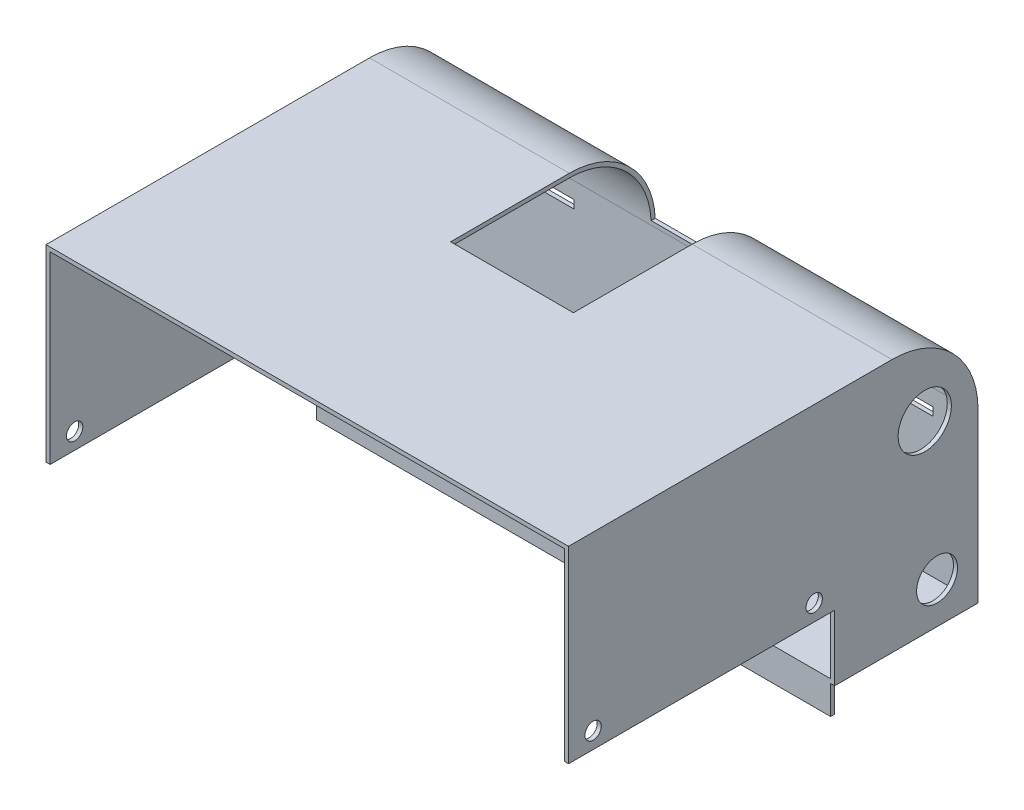
SolidWorks part; units mm, degrees
ref_plane "前视基准面" through (0, 0, 0) normal (0, 0, 1) x (1, 0, 0)
ref_plane "上视基准面" through (0, 0, 0) normal (0, 1, 0) x (1, 0, 0)
ref_plane "右视基准面" through (0, 0, 0) normal (1, 0, 0) x (0, 0, -1)
sketch "草图1" plane through (0, 0, 0) normal (1, 0, 0) x (0, 0, -1)
  line L0 (0, 0) -> (0, 41)
  line L1 (-21, 62) -> (-100, 62)
  line L2 (-100, 62) -> (-100, 61)
  line L6 (0, 0) -> (-34, 0)
  line L7 (-35, -7) -> (-35, 1)
  line L8 (-35, 1) -> (-1, 1)
  line L9 (-1, 1) -> (-1, 41)
  line L10 (-21, 61) -> (-100, 61)
  line L11 (-34, 0) -> (-34, -7)
  line L12 (-34, -7) -> (-35, -7)
  arc A0 (-1, 41) -> (-21, 61) centre (-21, 41) ccw
  arc A1 (0, 41) -> (-21, 62) centre (-21, 41) ccw
  point P15 (0, 62)
  dimension "D7" = 20
  dimension "D8" = 21
  dimension "D1" = 1
  dimension "D2" = 34
  dimension "D3" = 1
  dimension "D4" = 60
  dimension "D5" = 100
  dimension "D6" = 1
  dimension "D9" = 8
  dimension "D10" = 1
extrude "凸台-拉伸1" add sketch "草图1" along normal blind 125.6
sketch "草图2" plane through (0, 0, 0) normal (-1, 0, 0) x (0, 0, 1)
  line L1 (0, 0) -> (0, 41) construction
  line L2 (21, 62) -> (100, 62) construction
  line L3 (35, 0) -> (0, 0)
  line L4 (0, 0) -> (0, 41)
  line L5 (21, 62) -> (100, 62)
  line L6 (100, 62) -> (100, 16)
  line L7 (100, 16) -> (35, 16)
  line L8 (35, 16) -> (35, 0)
  line L9 (35, 1) -> (35, -7) construction
  line L10 (34, 0) -> (0, 0) construction
  line L11 (40, 20) -> (94, 20) construction
  arc A0 (21, 62) -> (0, 41) centre (21, 41) ccw construction
  arc A1 (21, 62) -> (0, 41) centre (21, 41) ccw
  circle A2 centre (94, 20) radius 2
  circle A3 centre (40, 20) radius 2
  dimension "D2" = 4
  dimension "D3" = 4
  dimension "D4" = 54
  dimension "D6" = 20
  dimension "D1" = 16
  dimension "D5" = 5
extrude "凸台-拉伸2" add sketch "草图2" along normal blind 1
sketch "草图3" plane through (125.6, 0, 0) normal (1, 0, 0) x (0, 0, -1)
  line L0 (-35, 16) -> (-100, 16) construction
  line L1 (-35, 0) -> (-35, 16) construction
  line L2 (0, 0) -> (-35, 0) construction
  line L3 (0, 41) -> (0, 0) construction
  line L4 (-100, 62) -> (-21, 62) construction
  line L5 (-100, 16) -> (-100, 62) construction
  line L6 (-35, 16) -> (-100, 16)
  line L7 (-35, 0) -> (-35, 16)
  line L8 (0, 0) -> (-35, 0)
  line L9 (0, 41) -> (0, 0)
  line L10 (-100, 62) -> (-21, 62)
  line L11 (-100, 16) -> (-100, 62)
  circle A0 centre (-94, 20) radius 2 construction
  circle A1 centre (-40, 20) radius 2 construction
  arc A2 (0, 41) -> (-21, 62) centre (-21, 41) ccw construction
  circle A3 centre (-94, 20) radius 2
  circle A4 centre (-40, 20) radius 2
  arc A5 (0, 41) -> (-21, 62) centre (-21, 41) ccw
  circle A6 centre (-13, 45) radius 6.5
  circle A7 centre (-10, 10) radius 5
  dimension "D1" = 13
  dimension "D2" = 10
  dimension "D3" = 13
  dimension "D4" = 45
  dimension "D5" = 10
  dimension "D6" = 10
extrude "凸台-拉伸3" add sketch "草图3" along normal blind 1
sketch "草图4" plane through (0, 62, 0) normal (0, 1, 0) x (1, 0, 0)
  line L0 (62.8, -100) -> (62.8, 31.7599) construction
  line L1 (126.6, -100) -> (-1, -100) construction
  line L2 (47.8, -50) -> (77.8, -50)
  line L3 (77.8, -50) -> (77.8, 0)
  line L4 (77.8, 0) -> (47.8, 0)
  line L5 (47.8, -50) -> (47.8, 0)
  line L6 (126.6, 0) -> (-1, 0) construction
  point P8 (62.8, 0)
  dimension "D1" = 30
  dimension "D2" = 50
extrude "切除-拉伸1" cut sketch "草图4" against normal blind 20
sketch "草图5" plane through (0, 0, 0) normal (0, 0, -1) x (-1, 0, 0)
  line L0 (-62.8, 0) -> (-62.8, 69.7654) construction
  line L1 (-116.6, 37) -> (-96.6, 37)
  line L2 (-116.6, 37) -> (-116.6, 35)
  line L3 (-116.6, 35) -> (-96.6, 35)
  line L4 (-96.6, 37) -> (-96.6, 35)
  line L5 (-126.6, 0) -> (1, 0) construction
  line L6 (-29, 37) -> (-29, 35)
  line L7 (-9, 35) -> (-29, 35)
  line L8 (-9, 37) -> (-9, 35)
  line L9 (-9, 37) -> (-29, 37)
  line L10 (-126.6, 0) -> (-126.6, 41) construction
  line L11 (-126.6, 41) -> (1, 41) construction
  dimension "D1" = 2
  dimension "D2" = 20
  dimension "D3" = 10
  dimension "D4" = 4
extrude "切除-拉伸2" cut sketch "草图5" against normal up to next
sketch "草图6" plane through (126.6, 0, 0) normal (1, 0, 0) x (0, 0, -1)
  line L0 (-10, 16) -> (0, 16)
  line L1 (0, 0) -> (0, 41) construction
  line L2 (0, 16) -> (0, 4)
  line L3 (0, 4) -> (-10, 4)
  line L4 (-11.5529, 15.7956) -> (-11.1647, 14.3467)
  line L5 (-11.1647, 5.6533) -> (-11.5529, 4.2044)
  line L6 (-10, 10) -> (-10, 22.6843) construction
  line L7 (-11.1647, 5.6533) -> (-10, 10) construction
  line L8 (-10, 10) -> (-11.1647, 14.3467) construction
  arc A0 (-11.1647, 5.6533) -> (-11.1647, 14.3467) centre (-10, 10) ccw
  arc A1 (-10, 16) -> (-11.5529, 15.7956) centre (-10, 10) ccw
  arc A2 (-11.5529, 4.2044) -> (-10, 4) centre (-10, 10) ccw
  dimension "D1" = 9
  dimension "D2" = 12
  dimension "D3" = 15
  dimension "D4" = 165
extrude "凸台-拉伸4" add sketch "草图6" against normal blind 10 from offset 23
